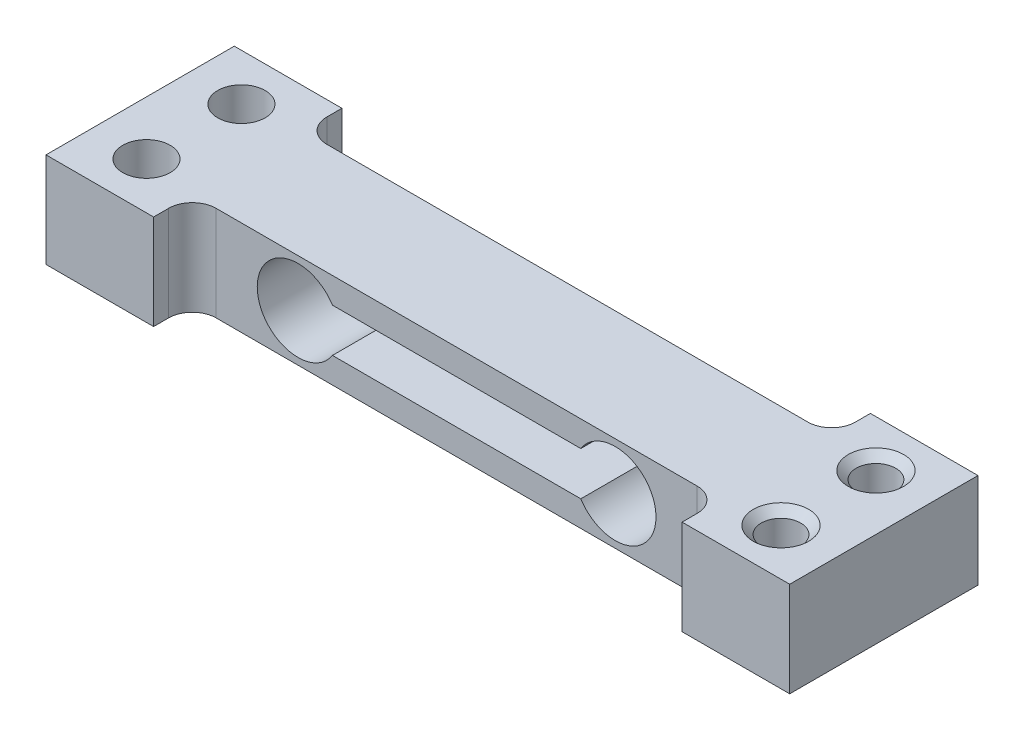
SolidWorks part; units mm, degrees
ref_plane "Front Plane" through (0, 0, 0) normal (0, 0, 1) x (1, 0, 0)
ref_plane "Top Plane" through (0, 0, 0) normal (0, 1, 0) x (1, 0, 0)
ref_plane "Right Plane" through (0, 0, 0) normal (1, 0, 0) x (0, 0, -1)
sketch "Sketch1" plane through (0, 0, 0) normal (0, 1, 0) x (1, 0, 0)
  line L0 (0, -3.5) -> (0, 3.5)
  line L1 (0, 3.5) -> (15.2, 3.5)
  line L2 (16.7, 5) -> (16.7, 5.95)
  line L3 (16.7, 5.95) -> (23.5, 5.95)
  line L4 (23.5, 5.95) -> (23.5, -5.95)
  line L5 (23.5, -5.95) -> (16.7, -5.95)
  line L6 (16.7, -5) -> (16.7, -5.95)
  line L7 (15.2, -3.5) -> (0, -3.5)
  line L8 (0, 0) -> (0, 50000) construction
  line L9 (0, 0) -> (50000, 0) construction
  arc A0 (15.2, 3.5) -> (16.7, 5) centre (15.2, 5) ccw
  arc A1 (16.7, -5) -> (15.2, -3.5) centre (15.2, -5) ccw
  point P4 (0, 0)
  dimension "D1" = 11.9
  dimension "D4" = 1.5
  dimension "D2" = 47
  dimension "D3" = 7
  dimension "D5" = 6.8
extrude "Boss-Extrude1" add sketch "Sketch1" along normal mid plane 6
sketch "Sketch2" plane through (0, 0, 3.5) normal (0, 0, 1) x (1, 0, 0)
  line L0 (0, 3) -> (0, -3) construction
  line L1 (-10.025, -1.375) -> (10.025, -1.375)
  line L2 (-10.025, -1.375) -> (-10.025, 1.375)
  line L3 (-10.025, 1.375) -> (10.025, 1.375)
  line L4 (10.025, -1.375) -> (10.025, 1.375)
  line L5 (-10.025, -1.375) -> (10.025, 1.375) construction
  line L6 (-10.025, 1.375) -> (10.025, -1.375) construction
  circle A0 centre (10.025, 0) radius 2.575
  point P0 (0, 0)
  line M6 (0, 3) -> (0, -3)
  dimension "D1" = 5.15
  dimension "D2" = 20.05
  dimension "D3" = 2.75
extrude "Cut-Extrude1" cut sketch "Sketch2" against normal through all contours L1 A0 L3 L4 | L3 A0 L1 L4 | A0 L3 L1 M6
sketch "Sketch3" plane through (0, 3, 0) normal (0, 1, 0) x (1, 0, 0)
  line L0 (0, 3.5) -> (0, -3.5) construction
  line L1 (-20, 3) -> (20, 3) construction
  line L2 (-20, 3) -> (-20, -3) construction
  line L3 (-20, -3) -> (20, -3) construction
  line L4 (20, 3) -> (20, -3) construction
  line L5 (-20, 3) -> (20, -3) construction
  line L6 (-20, -3) -> (20, 3) construction
  point P0 (0, 0)
  dimension "D1" = 40
  dimension "D2" = 6
mirror "Mirror1" about plane through (0, 0, 0) normal (1, 0, 0) of bodies 102 103
hole_wizard "M3 Tapped Hole1" positions "Sketch4" profile "Sketch5" tap size "M3" standard "DIN" end condition through all
sketch "Sketch4" plane through (0, 3, 0) normal (0, 1, 0) x (1, 0, 0)
  point P0 (20, 3)
  point P3 (20, -3)
cosmetic thread "Hole Thread1" parameters "D2"=3
cosmetic thread "Hole Thread2" parameters "D2"=3
sketch "Sketch5" plane through (20, 3, -3) normal (1, 0, 0) x (0, 0, 1)
  line L0 (0, 0) -> (0, 6)
  line L1 (0, 6) -> (1.75, 6)
  line L2 (1.25, 5.5) -> (1.25, 0.5)
  line L3 (1.25, 0.5) -> (1.75, 0)
  line L5 (1.75, 0) -> (0, 0)
  line L6 (-1.25, 0.5) -> (-1.75, 0) construction
  line L7 (1.75, 6) -> (1.25, 5.5)
  line L8 (-1.75, 6) -> (-1.25, 5.5) construction
  line L11 (0, -6.35) -> (0, 107.95) construction
  dimension "Thru Tap Drill Dia." = 2.5
  dimension "Thru Tap Drill Depth" = 6
  dimension "Near C'Sink Dia." = 3.5
  dimension "Near C'Sink Angle" = 90
  dimension "Far C'Sink Dia." = 3.5
  dimension "Far C'Sink Angle" = 90
sketch "Sketch6" plane through (0, 3, 0) normal (0, 1, 0) x (1, 0, 0)
  line L0 (0, 0) -> (-20.1, 0) construction
  line L1 (-20.1, -3) -> (-20.1, 3) construction
  line L2 (-23.5, 5.95) -> (-16.7, 5.95) construction
  circle A0 centre (-20.1, 3) radius 1.5
  circle A1 centre (-20.1, -3) radius 1.5
  point P8 (-20.1, 5.95)
  dimension "D2" = 3
  dimension "D3" = 3
  dimension "D1" = 6
extrude "Cut-Extrude2" cut sketch "Sketch6" against normal through all
